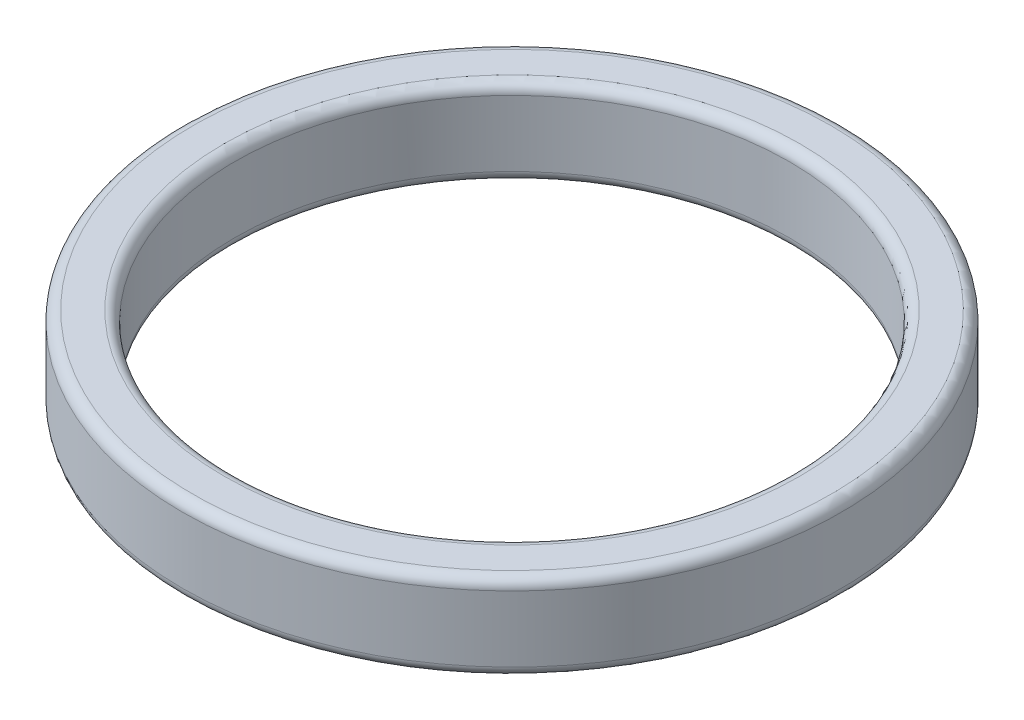
SolidWorks part; units mm, degrees
material "EPDM 60 дюрометр"
ref_plane "Спереди" through (0, 0, 0) normal (0, 0, 1) x (1, 0, 0)
ref_plane "Сверху" through (0, 0, 0) normal (0, 1, 0) x (1, 0, 0)
ref_plane "Справа" through (0, 0, 0) normal (1, 0, 0) x (0, 0, -1)
sketch "Эскиз1" plane through (0, 0, 0) normal (0, 0, 1) x (1, 0, 0)
  line L0 (0, 0) -> (0, 2.5) construction
  line L2 (-9.5, 2.5) -> (-8, 2.5)
  line L3 (-9.5, 2.5) -> (-9.5, 0)
  line L4 (-9.5, 0) -> (-8, 0)
  line L5 (-8, 2.5) -> (-8, 0)
  dimension "D1" = 2.5
  dimension "D2" = 19
  dimension "D3" = 16
revolve "Повернуть1" add sketch "Эскиз1" angle 360 about L0
fillet "Скругление1" radius 0.3 4 edges at (0, 0, -9.5) (0, 0, -8) (0, 2.5, -9.5) (0, 2.5, -8)
